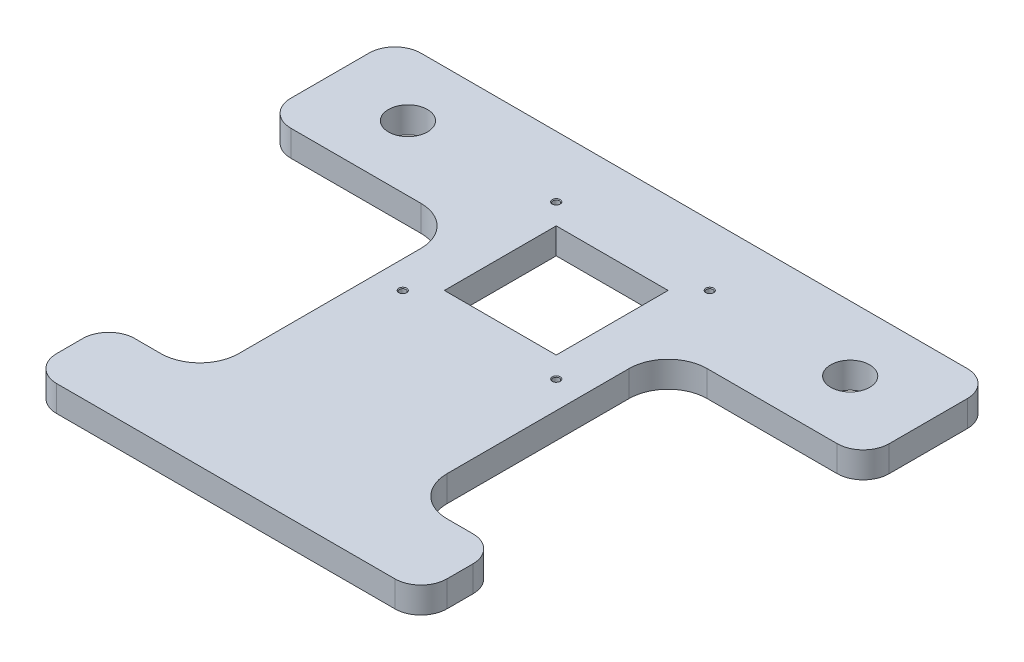
SolidWorks part; units mm, degrees
ref_plane "Vorne" through (0, 0, 0) normal (0, 0, 1) x (1, 0, 0)
ref_plane "Oben" through (0, 0, 0) normal (0, 1, 0) x (1, 0, 0)
ref_plane "Rechts" through (0, 0, 0) normal (1, 0, 0) x (0, 0, -1)
ref_plane "E_Boden" through (0, 1, 0) normal (0, 1, 0) x (1, 0, 0)
sketch "Skizze1" plane through (0, 0, 0) normal (0, 1, 0) x (1, 0, 0)
  line L0 (0, -84.2382) -> (0, 127.1868) construction
  line L1 (-165.4867, 0) -> (188.3198, 0) construction
  line L2 (-105, 90) -> (105, 90)
  line L3 (-115, 80) -> (-115, 50)
  line L8 (-105, 40) -> (-55, 40)
  line L9 (-40, 25) -> (-40, -45)
  line L10 (-55, -60) -> (-65, -60)
  line L11 (-75, -70) -> (-75, -80)
  line L12 (-65, -90) -> (65, -90)
  line L13 (75, -70) -> (75, -80)
  line L14 (55, -60) -> (65, -60)
  line L15 (40, 25) -> (40, -45)
  line L16 (105, 40) -> (55, 40)
  line L17 (115, 80) -> (115, 50)
  arc A0 (40, 25) -> (55, 40) centre (55, 25) cw
  arc A1 (55, -60) -> (40, -45) centre (55, -45) cw
  arc A2 (-40, -45) -> (-55, -60) centre (-55, -45) cw
  arc A3 (-55, 40) -> (-40, 25) centre (-55, 25) cw
  arc A4 (75, -70) -> (65, -60) centre (65, -70) ccw
  arc A5 (75, -80) -> (65, -90) centre (65, -80) cw
  arc A6 (-75, -80) -> (-65, -90) centre (-65, -80) ccw
  arc A7 (-65, -60) -> (-75, -70) centre (-65, -70) ccw
  arc A8 (-115, 50) -> (-105, 40) centre (-105, 50) ccw
  arc A9 (105, 40) -> (115, 50) centre (105, 50) ccw
  arc A10 (115, 80) -> (105, 90) centre (105, 80) ccw
  arc A11 (-105, 90) -> (-115, 80) centre (-105, 80) ccw
  point P15 (0, -90)
  point P16 (0, 90)
  point P22 (40, 40)
  point P25 (40, -60)
  point P28 (-40, -60)
  point P31 (-40, 40)
  point P34 (75, -60)
  point P37 (75, -90)
  point P40 (-75, -90)
  point P43 (-75, -60)
  point P46 (-115, 40)
  point P49 (115, 40)
  point P52 (115, 90)
  point P55 (-115, 90)
  dimension "D7" = 15
  dimension "D8" = 10
  dimension "D1" = 230
  dimension "D2" = 50
  dimension "D3" = 130
  dimension "D4" = 150
  dimension "D5" = 80
  dimension "D6" = 30
extrude "Aufsatz-Linear austragen1" add sketch "Skizze1" along normal blind 10
hole_wizard "Ø15.0 (15) Durchmesser Bohrung1" positions "Skizze6" profile "Skizze7" hole size "Ø15.0" standard "DIN" end condition through all
sketch "Skizze6" plane through (0, 10, 0) normal (0, 1, 0) x (1, 0, 0)
  line L2 (105, 90) -> (-105, 90) construction
  line L3 (0, 90) -> (0, -90) construction
  line L4 (-65, -90) -> (65, -90) construction
  point P0 (-85, 65)
  point P2 (85, 65)
  dimension "D1" = 25
  dimension "D2" = 25
  dimension "D3" = 170
sketch "Skizze7" plane through (-85, 10, -65) normal (1, 0, 0) x (0, 0, 1)
  line L0 (0, 0) -> (0, 10)
  line L1 (0, 10) -> (7.5, 10)
  line L2 (7.5, 10) -> (7.5, 0)
  line L5 (7.5, 0) -> (0, 0)
  line L11 (0, -6.35) -> (0, 107.95) construction
  dimension "Bohrerdurchmesser" = 15
  dimension "Bohrungstiefe" = 10
sketch "Skizze8" plane through (0, 10, 0) normal (0, 1, 0) x (1, 0, 0)
  line L0 (0, 90) -> (0, -90) construction
  line L1 (-39.1455, 37) -> (35.4895, 37) construction
  line L3 (105, 90) -> (-105, 90) construction
  line L4 (-21.5, 58.5) -> (21.5, 58.5)
  line L5 (-21.5, 58.5) -> (-21.5, 15.5)
  line L6 (-21.5, 15.5) -> (21.5, 15.5)
  line L7 (21.5, 58.5) -> (21.5, 15.5)
  line L8 (-65, -90) -> (65, -90) construction
  dimension "D1" = 43
  dimension "D2" = 43
  dimension "D3" = 53
extrude "Schnitt-Linear austragen2" cut sketch "Skizze8" against normal blind 10
hole_wizard "M3 Gewindebohrung1" positions "Skizze9" profile "Skizze10" tap size "M3" standard "DIN"
sketch "Skizze9" plane through (0, 10, 0) normal (0, 1, 0) x (1, 0, 0)
  line L0 (0, 58.5) -> (0, 15.5) construction
  line L1 (21.5, 58.5) -> (-21.5, 58.5) construction
  line L2 (-21.5, 15.5) -> (21.5, 15.5) construction
  line L4 (-21.5, 37) -> (21.5, 37) construction
  line L5 (-21.5, 58.5) -> (-21.5, 15.5) construction
  line L6 (21.5, 15.5) -> (21.5, 58.5) construction
  point P0 (-29.5, 66.5)
  point P2 (-29.5, 7.5)
  point P4 (29.5, 7.5)
  point P6 (29.5, 66.5)
  dimension "D1" = 8
  dimension "D2" = 8
sketch "Skizze10" plane through (-29.5, 10, -66.5) normal (1, 0, 0) x (0, 0, 1)
  line L0 (0, 0) -> (0, 8.7511)
  line L1 (0, 8.7511) -> (1.25, 8)
  line L2 (1.25, 8) -> (1.25, 0.275)
  line L3 (1.25, 0.275) -> (1.525, 0)
  line L5 (1.525, 0) -> (0, 0)
  line L6 (-1.25, 0.275) -> (-1.525, 0) construction
  line L10 (0, 8.7511) -> (-1.25, 8) construction
  line L11 (0, -6.35) -> (0, 107.95) construction
  dimension "Bohrerdurchmesser" = 2.5
  dimension "Bohrungstiefe" = 8
  dimension "Senkdurchmesser (Oben)" = 3.05
  dimension "Senkwinkel (Oben)" = 90
  dimension "Spitzenwinkel" = 118
cosmetic thread "Bohrungsgewinde1" parameters "D1"=6, "D2"=3
cosmetic thread "Bohrungsgewinde2" parameters "D1"=6, "D2"=3
cosmetic thread "Bohrungsgewinde3" parameters "D1"=6, "D2"=3
cosmetic thread "Bohrungsgewinde4" parameters "D1"=6, "D2"=3
